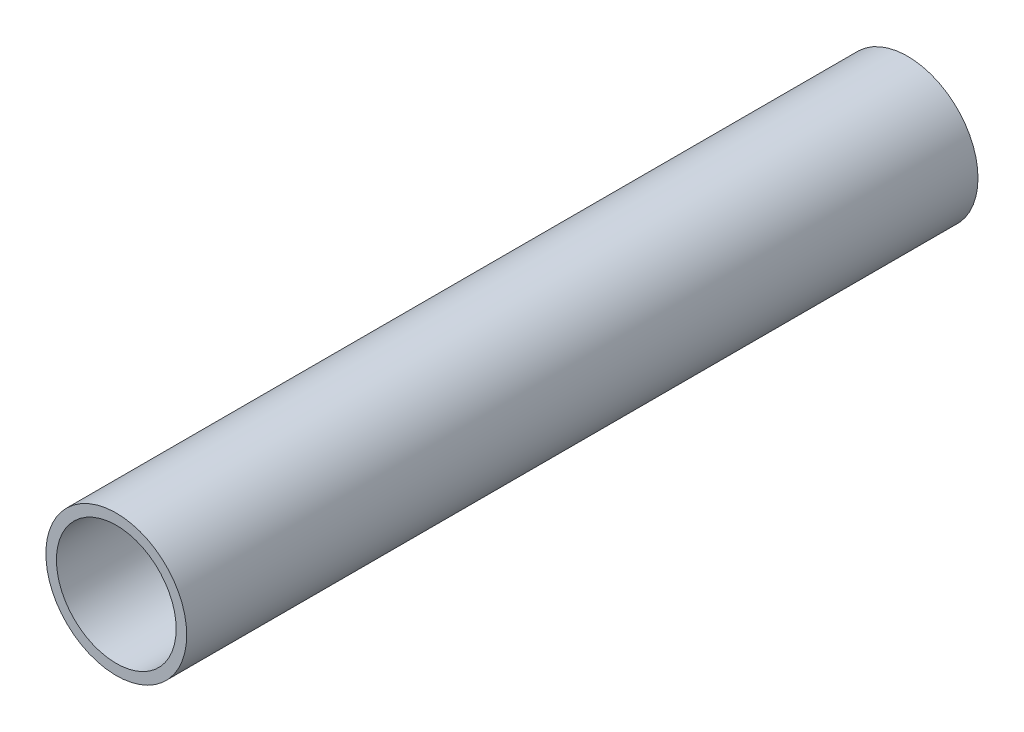
SolidWorks part; units mm, degrees
ref_plane "Front Plane" through (0, 0, 0) normal (0, 0, 1) x (1, 0, 0)
ref_plane "Top Plane" through (0, 0, 0) normal (0, 1, 0) x (1, 0, 0)
ref_plane "Right Plane" through (0, 0, 0) normal (1, 0, 0) x (0, 0, -1)
sketch "Sketch1" plane through (0, 0, 0) normal (0, 0, 1) x (1, 0, 0)
  circle A0 centre (0, 0) radius 13.35
  dimension "D1" = 26.7
extrude "Extrude-Thin1" add sketch "Sketch1" along normal mid plane 150 thin thin type one direction reverse wall 2
